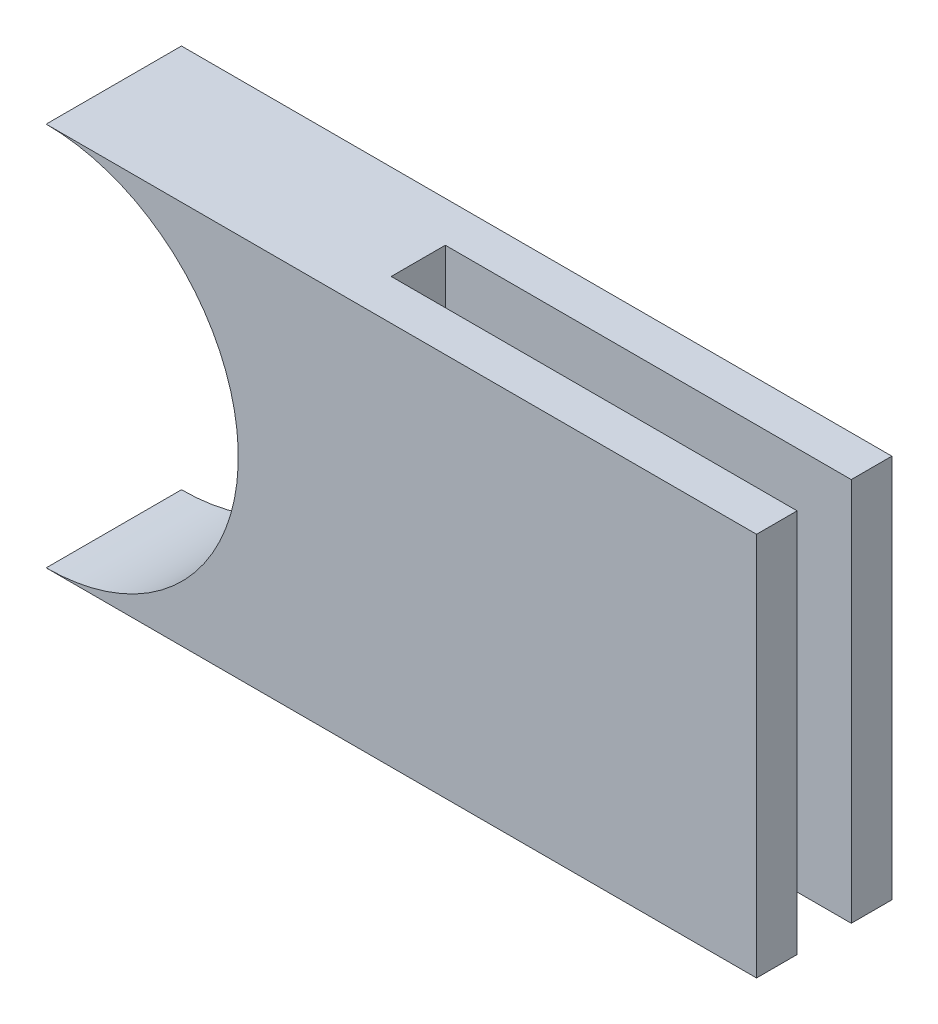
SolidWorks part; units mm, degrees
ref_plane "Front Plane" through (0, 0, 0) normal (0, 0, 1) x (1, 0, 0)
ref_plane "Top Plane" through (0, 0, 0) normal (0, 1, 0) x (1, 0, 0)
ref_plane "Right Plane" through (0, 0, 0) normal (1, 0, 0) x (0, 0, -1)
sketch "Sketch1" plane through (0, 0, 0) normal (0, 0, 1) x (1, 0, 0)
  circle A0 centre (0, 0) radius 19.939
  dimension "D1" = 39.878
extrude "circle extrude" add sketch "Sketch1" along normal blind 12.7
sketch "Sketch3" plane through (0, 0, 0) normal (1, 0, 0) x (0, 0, -1)
  line L0 (0, 19.8374) -> (0, -19.8374) construction
  line L1 (-12.7, 19.939) -> (0, 19.939)
  line L2 (-12.7, 19.939) -> (-12.7, -19.939)
  line L3 (-12.7, -19.939) -> (0, -19.939)
  line L4 (0, 19.939) -> (0, -19.939)
  line L5 (-12.7, -19.939) -> (0, -19.939) construction
extrude "rectangle extrude" add sketch "Sketch3" along normal blind 68.58
sketch "Sketch2" plane through (0, 0, 12.7) normal (0, 0, 1) x (1, 0, 0)
  circle A0 centre (0, 0) radius 18.034
  dimension "D1" = 36.068
extrude "cricle cut" cut sketch "Sketch2" against normal through all
sketch "Sketch4" plane through (0, 0, 12.7) normal (0, 0, 1) x (1, 0, 0)
  line L0 (68.58, 19.939) -> (68.58, -19.939) construction
  line L1 (0, 18.034) -> (66.675, 18.034)
  line L2 (0, 18.034) -> (0, -18.034)
  line L3 (0, -18.034) -> (66.675, -18.034)
  line L4 (66.675, 18.034) -> (66.675, -18.034)
  line L5 (68.58, -19.939) -> (0, -19.939) construction
  circle A0 centre (0, 0) radius 18.034 construction
  dimension "D1" = 1.905
  dimension "D2" = 1.905
extrude "frame cut" cut sketch "Sketch4" against normal through all flip side to cut
sketch "Sketch8" plane through (0, 0, 12.7) normal (0, 0, 1) x (1, 0, 0)
  line L6 (0, -18.034) -> (66.675, -18.034) construction
  line L7 (36.068, 18.034) -> (66.675, 18.034)
  line L8 (66.675, 18.034) -> (66.675, -18.034)
  line L9 (66.675, -18.034) -> (36.068, -18.034)
  line L10 (66.675, 18.034) -> (0, 18.034) construction
  arc A1 (36.068, -18.034) -> (36.068, 18.034) centre (36.068, 0) ccw
  dimension "D1" = 36.068
extrude "end cut" [suppressed] cut sketch "Sketch8" against normal through all
sketch "Sketch10" plane through (0, 0, 0) normal (0, 0, -1) x (-1, 0, 0)
  line L2 (0, 18.034) -> (-66.675, 18.034)
  line L3 (-66.675, -18.034) -> (0, -18.034)
  line L4 (0, 18.034) -> (-66.675, 18.034)
  line L5 (-66.675, -18.034) -> (0, -18.034)
  line L7 (-66.675, 18.034) -> (-66.675, -18.034)
  line L8 (-66.675, 18.034) -> (-66.675, -18.034)
  arc A3 (0, 18.034) -> (0, -18.034) centre (0, 0) ccw
  arc A5 (0, 18.034) -> (0, -18.034) centre (0, 0) ccw
  dimension "D1" = 0
extrude "extension" [suppressed] add sketch "Sketch10" along normal blind 2.54
ref_plane "Plane2" [suppressed] through (20.32, 0, 0) normal (1, 0, 0) x (0, 0, -1)
sketch "Sketch11" [suppressed] plane through (20.32, 0, 0) normal (1, 0, 0) x (0, 0, -1)
  line L0 (2.54, 18.034) -> (-7.62, 18.034) construction
  line L1 (0, -18.034) -> (-5.08, -18.034)
  line L2 (0, -18.034) -> (0, 18.034)
  line L3 (0, 18.034) -> (-5.08, 18.034)
  line L4 (-5.08, -18.034) -> (-5.08, 18.034)
  line L5 (0, -18.034) -> (-5.08, 18.034) construction
  line L6 (0, 18.034) -> (-5.08, -18.034) construction
  line L7 (2.54, -18.034) -> (-7.62, -18.034) construction
  point P0 (-2.54, 0)
  dimension "D1" = 2.54
  dimension "D2" = 5.08
extrude "middle" [suppressed] cut sketch "Sketch11" along normal through all
sketch "Sketch12" [suppressed] plane through (0, 0, 0) normal (0, 0, 1) x (1, 0, 0)
  line L0 (20.32, -5.588) -> (20.32, 5.588) construction
  line L1 (0, 18.034) -> (61.595, 18.034) construction
  line L2 (2.286, 18.034) -> (0, 18.034)
  line L3 (0, 18.034) -> (0, -18.034)
  line L4 (0, -18.034) -> (2.286, -18.034)
  arc A0 (2.286, -18.034) -> (2.286, 18.034) centre (2.286, 0) ccw
  dimension "D1" = 36.068
extrude "circle extension" [suppressed] cut sketch "Sketch12" along normal blind 5.08 flip side to cut
sketch "Sketch13" plane through (66.675, 0, 0) normal (1, 0, 0) x (0, 0, -1)
  line L1 (-3.81, -18.034) -> (-8.89, -18.034)
  line L2 (-3.81, -18.034) -> (-3.81, 18.034)
  line L3 (-3.81, 18.034) -> (-8.89, 18.034)
  line L4 (-8.89, -18.034) -> (-8.89, 18.034)
  line L5 (-3.81, -18.034) -> (-8.89, 18.034) construction
  line L6 (-3.81, 18.034) -> (-8.89, -18.034) construction
  line L7 (0, -18.034) -> (-12.7, -18.034) construction
  line L8 (0, 18.034) -> (-12.7, 18.034) construction
  point P0 (-6.35, 0)
  dimension "D1" = 6.35
  dimension "D2" = 5.08
extrude "back cut" cut sketch "Sketch13" against normal blind 38.1
sketch "Sketch14" plane through (28.575, 0, 0) normal (1, 0, 0) x (0, 0, -1)
  circle A0 centre (-6.35, 0) radius 1.905
  dimension "D2" = 3.81
  dimension "D1" = 6.35
extrude "for spring extrude" add sketch "Sketch14" along normal blind 2.54
equation "\"wall_thickness\"= 0.125in"
equation "\"base_thickness\"= 0.25in"
